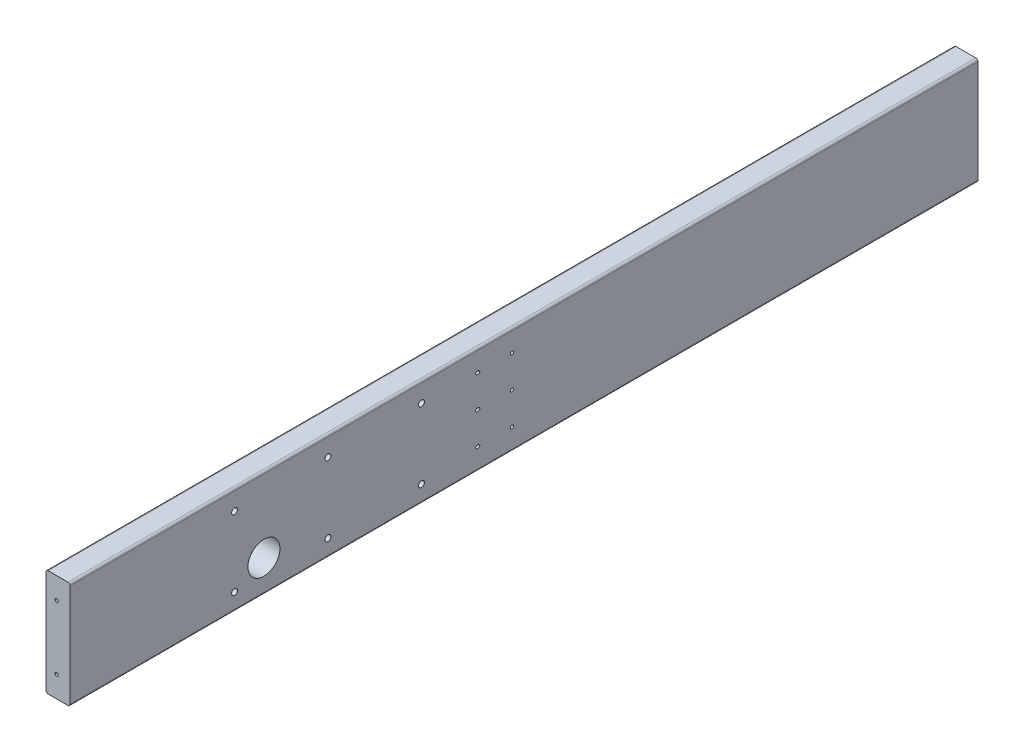
SolidWorks part; units mm, degrees
material "Beech"
ref_plane "Front Plane" through (0, 0, 0) normal (0, 0, 1) x (1, 0, 0)
ref_plane "Top Plane" through (0, 0, 0) normal (0, 1, 0) x (1, 0, 0)
ref_plane "Right Plane" through (0, 0, 0) normal (1, 0, 0) x (0, 0, -1)
sketch "Sketch1" plane through (0, 0, 0) normal (0, 0, 1) x (1, 0, 0)
  line L0 (-31.1883, 134.2727) -> (-31.1883, -65.7273)
  line L1 (-31.1883, -65.7273) -> (13.8117, -65.7273)
  line L2 (-31.1883, 134.2727) -> (13.8117, 134.2727)
  line L3 (13.8117, 134.2727) -> (13.8117, -65.7273)
extrude "Boss-Extrude1" add sketch "Sketch1" along normal blind 1700
fillet "Fillet1" radius 4 4 edges at (-31.1883, -65.7273, 850) (13.8117, -65.7273, 850) (-31.1883, 134.2727, 850) (13.8117, 134.2727, 850)
sketch "Sketch9" plane through (13.8117, 0, 0) normal (1, 0, 0) x (0, 0, -1)
  circle A0 centre (-1337, -5.7273) radius 30
extrude "Cut-Extrude1" cut sketch "Sketch9" against normal blind 50
sketch "Sketch10" plane through (13.8117, 0, 0) normal (1, 0, 0) x (0, 0, -1)
  circle A0 centre (-1392, 97.2727) radius 5.5
extrude "Cut-Extrude2" cut sketch "Sketch10" against normal blind 50
sketch "Sketch11" plane through (13.8117, 0, 0) normal (1, 0, 0) x (0, 0, -1)
  circle A0 centre (-1392, -33.7273) radius 5.5
extrude "Cut-Extrude3" cut sketch "Sketch11" against normal blind 50
sketch "Sketch12" plane through (13.8117, 0, 0) normal (1, 0, 0) x (0, 0, -1)
  circle A0 centre (-1217, 97.2727) radius 5.5
extrude "Cut-Extrude4" cut sketch "Sketch12" against normal blind 50
sketch "Sketch13" plane through (13.8117, 0, 0) normal (1, 0, 0) x (0, 0, -1)
  circle A0 centre (-1217, -33.7273) radius 5.5
extrude "Cut-Extrude5" cut sketch "Sketch13" against normal blind 50
sketch "Sketch14" plane through (13.8117, 0, 0) normal (1, 0, 0) x (0, 0, -1)
  circle A0 centre (-1042, -33.7273) radius 5.5
extrude "Cut-Extrude6" cut sketch "Sketch14" against normal blind 50
sketch "Sketch15" plane through (13.8117, 0, 0) normal (1, 0, 0) x (0, 0, -1)
  circle A0 centre (-1042, 97.2727) radius 5.5
extrude "Cut-Extrude7" cut sketch "Sketch15" against normal blind 50
sketch "Sketch16" plane through (-31.1883, 0, 0) normal (-1, 0, 0) x (0, 0, 1)
  line L0 (0, 130.2727) -> (0, -61.7273) construction
  line L1 (1700, 130.2727) -> (0, 130.2727) construction
  line L2 (1700, -65.7273) -> (0, -65.7273) construction
  circle A0 centre (50, -25.7273) radius 18
  circle A1 centre (50, 34.2727) radius 18
  circle A2 centre (50, 91.2727) radius 18
  dimension "D1" = 36
  dimension "D2" = 36
  dimension "D3" = 36
  dimension "D4" = 50
  dimension "D5" = 50
  dimension "D6" = 50
  dimension "D7" = 39
  dimension "D8" = 40
  dimension "D9" = 100
extrude "Cut-Extrude8" cut sketch "Sketch16" against normal blind 30
hole_wizard "Ø8.0mm Dowel Slot3" positions "Sketch19" profile "Sketch20" size "Ø8.0" standard "ISO"
sketch "Sketch19" plane through (793.8117, -65.7273, 0) normal (0, 0, 1) x (1, 0, 0)
  point P0 (-802.5, 40)
  point P2 (-802.5, 100)
  point P4 (-802.5, 157)
sketch "Sketch20" plane through (-8.6883, -25.7273, 0) normal (1, 0, 0) x (0, -1, 0)
  line L0 (0, 0) -> (0, 140)
  line L1 (0, 140) -> (4, 137.5966)
  line L2 (4, 137.5966) -> (4, 0.025)
  line L3 (4, 0.025) -> (4.025, 0)
  line L4 (4.025, 0) -> (0, 0)
  line L5 (-4, 0.025) -> (-4.025, 0) construction
  line L6 (0, 140) -> (-4, 137.5966) construction
  line L7 (0, -6.35) -> (0, 107.95) construction
  dimension "Hole Dia." = 8
  dimension "Hole Depth" = 140
  dimension "Near C'Sink Dia." = 8.05
  dimension "Near C'Sink Angle" = 90
  dimension "Drill Angle" = 118
hole_wizard "Ø6.0mm Dowel Slot" positions "Sketch21" profile "Sketch22" size "Ø6.0" standard "ISO" slot yes
sketch "Sketch21" plane through (-854.1534, -65.7273, 36.0493) normal (-0.7661, 0, 0.6428) x (0.6428, 0, 0.7661)
  line L1 (1244.85, 160) -> (1250.85, 160) construction
  point P0 (1247.85, 160)
  point P2 (1247.85, 100)
  point P4 (1247.85, 40)
sketch "Sketch22" plane through (-52.0862, 94.2727, 991.9875) normal (0, 1, 0) x (0.6428, 0, 0.7661)
  line L0 (0, 0) -> (0, 130)
  line L1 (0, 130) -> (3, 128.1974)
  line L2 (3, 128.1974) -> (3, 0.025)
  line L3 (3, 0.025) -> (3.025, 0)
  line L4 (3.025, 0) -> (0, 0)
  line L5 (-3, 0.025) -> (-3.025, 0) construction
  line L6 (0, 130) -> (-3, 128.1974) construction
  line L7 (0, -6.35) -> (0, 107.95) construction
  dimension "Hole Dia." = 6
  dimension "Hole Depth" = 130
  dimension "Near C'Sink Dia." = 6.05
  dimension "Near C'Sink Angle" = 90
  dimension "Drill Angle" = 118
hole_wizard "Ø6.0mm Dowel Slot1" positions "Sketch23" profile "Sketch24" size "Ø6.0" standard "ISO" slot yes
sketch "Sketch23" plane through (13.8117, -65.7273, 0) normal (1, 0, 0) x (0, 0, -1)
  point P0 (-872.5, 160)
  point P2 (-872.5, 100)
  point P4 (-872.5, 40)
sketch "Sketch24" plane through (13.8117, 94.2727, 872.5) normal (0, 1, 0) x (0, 0, -1)
  line L0 (0, 0) -> (0, 65)
  line L1 (0, 65) -> (3, 63.1974)
  line L2 (3, 63.1974) -> (3, 0.025)
  line L3 (3, 0.025) -> (3.025, 0)
  line L4 (3.025, 0) -> (0, 0)
  line L5 (-3, 0.025) -> (-3.025, 0) construction
  line L6 (0, 65) -> (-3, 63.1974) construction
  line L7 (0, -6.35) -> (0, 107.95) construction
  dimension "Hole Dia." = 6
  dimension "Hole Depth" = 65
  dimension "Near C'Sink Dia." = 6.05
  dimension "Near C'Sink Angle" = 90
  dimension "Drill Angle" = 118
sketch "Sketch25" plane through (-31.1883, 0, 0) normal (-1, 0, 0) x (0, 0, 1)
  line L0 (1700, 130.2727) -> (1700, -61.7273) construction
  line L1 (0, 134.2727) -> (1700, 134.2727) construction
  line L2 (1700, -65.7273) -> (0, -65.7273) construction
  circle A1 centre (1650, 94.2727) radius 18
  circle A2 centre (1650, -25.7273) radius 18
  dimension "D1" = 36
  dimension "D2" = 36
  dimension "D3" = 50
  dimension "D4" = 50
  dimension "D5" = 40
  dimension "D6" = 40
extrude "Cut-Extrude9" cut sketch "Sketch25" against normal blind 30
hole_wizard "Ø6.0mm Dowel Slot2" positions "Sketch26" profile "Sketch27" size "Ø6.0" standard "ISO" slot yes
sketch "Sketch26" plane through (-811.1883, -65.7273, 1700) normal (0, 0, 1) x (1, 0, 0)
  point P0 (25, 160)
  point P2 (25, 40)
  point P11 (800, 160)
  point P13 (800, 40)
sketch "Sketch27" plane through (-786.1883, 94.2727, 1700) normal (1, 0, 0) x (0, -1, 0)
  line L0 (0, 0) -> (0, 50)
  line L1 (0, 50) -> (3, 48.1974)
  line L2 (3, 48.1974) -> (3, 0.025)
  line L3 (3, 0.025) -> (3.025, 0)
  line L4 (3.025, 0) -> (0, 0)
  line L5 (-3, 0.025) -> (-3.025, 0) construction
  line L6 (0, 50) -> (-3, 48.1974) construction
  line L7 (0, -6.35) -> (0, 107.95) construction
  dimension "Hole Dia." = 6
  dimension "Hole Depth" = 50
  dimension "Near C'Sink Dia." = 6.05
  dimension "Near C'Sink Angle" = 90
  dimension "Drill Angle" = 118
hole_wizard "Ø8.0mm Dowel Slot4" positions "Sketch30" profile "Sketch31" size "Ø8.0" standard "ISO" slot yes
sketch "Sketch30" plane through (-811.1883, -65.7273, -90) normal (0, 0, -1) x (-1, 0, 0)
  point P0 (-802.5, 40)
  point P2 (-802.5, 100)
  point P4 (-802.5, 157)
sketch "Sketch31" plane through (-8.6883, -25.7273, -90) normal (1, 0, 0) x (0, 1, 0)
  line L0 (0, 0) -> (0, 140)
  line L1 (0, 140) -> (4, 137.5966)
  line L2 (4, 137.5966) -> (4, 0.025)
  line L3 (4, 0.025) -> (4.025, 0)
  line L4 (4.025, 0) -> (0, 0)
  line L5 (-4, 0.025) -> (-4.025, 0) construction
  line L6 (0, 140) -> (-4, 137.5966) construction
  line L7 (0, -6.35) -> (0, 107.95) construction
  dimension "Hole Dia." = 8
  dimension "Hole Depth" = 140
  dimension "Near C'Sink Dia." = 8.05
  dimension "Near C'Sink Angle" = 90
  dimension "Drill Angle" = 118
ref_plane "Plane1" through (0, 34.2727, 0) normal (0, 1, 0) x (1, 0, 0)
hole_wizard "Ø6.0mm Dowel Slot4" positions "Sketch34" profile "Sketch35" size "Ø6.0" standard "ISO"
sketch "Sketch34" plane through (-811.1883, 146.2727, 0) normal (0, 1, 0) x (1, 0, 0)
  point P0 (22.5, 1812.5)
  point P3 (22.5, 1777.0533)
  point P7 (802.5, 1812.5)
  point P10 (802.5, 1787.0555)
  point P14 (22.5608, 973.75)
  point P17 (22.5608, 951.25)
  point P20 (802.5608, 973.75)
  point P23 (802.5608, 951.25)
  point P26 (22.5, -1455.8975)
  point P28 (802.5, -1462.0727)
  point P30 (802.5, -861.25)
  point P33 (802.5, -883.75)
  point P36 (22.5, -861.25)
  point P39 (22.5, -883.75)
  point P42 (22.5, 67.5)
  point P46 (22.5, 22.5)
  point P50 (802.5, 67.5)
  point P52 (802.5, 22.5)
sketch "Sketch35" plane through (-788.6883, 146.2727, -1812.5) normal (1, 0, 0) x (0, 0, 1)
  line L0 (0, 0) -> (0, 30)
  line L1 (0, 30) -> (3, 28.1974)
  line L2 (3, 28.1974) -> (3, 0.025)
  line L3 (3, 0.025) -> (3.025, 0)
  line L4 (3.025, 0) -> (0, 0)
  line L5 (-3, 0.025) -> (-3.025, 0) construction
  line L6 (0, 30) -> (-3, 28.1974) construction
  line L7 (0, -6.35) -> (0, 107.95) construction
  dimension "Hole Dia." = 6
  dimension "Hole Depth" = 30
  dimension "Near C'Sink Dia." = 6.05
  dimension "Near C'Sink Angle" = 90
  dimension "Drill Angle" = 118
hole_wizard "Ø6.0mm Dowel Slot6" positions "Sketch38" profile "Sketch39" size "Ø6.0" standard "ISO"
sketch "Sketch38" plane through (-811.1883, 146.2727, 0) normal (0, 1, 0) x (1, 0, 0)
  point P0 (22.5, 1726.5)
  point P4 (22.5, 1640.5)
  point P6 (802.5, 1726.5)
  point P10 (802.5, 1640.5)
  point P12 (22.5, -955.9606)
  point P14 (22.5, -1636.5)
  point P16 (802.5, -1462.5)
  point P18 (802.5, -1636.5)
  point P19 (22.5, -1722.5)
  point P22 (802.5, -1722.5)
  point P25 (22.5, -1550.5)
  point P27 (802.5, -778.9107)
  point P33 (120, -1722.5)
  point P37 (217.5, -1722.5)
  point P39 (315, -1722.5)
  point P41 (412.5, -1722.5)
  point P43 (510, -1722.5)
  point P45 (607.5, -1722.5)
  point P48 (705, -1722.5)
  point P51 (22.5, -861.25)
  point P54 (22.5, -883.75)
  point P57 (-22.4962, -917.6022)
  point P60 (802.5, -861.25)
  point P63 (802.5, -883.75)
  point P66 (847.4962, -917.6022)
  point P69 (802.5, -536.8366)
  point P71 (22.5, -750.2496)
  point P73 (-341.0052, -650.3187)
  point P76 (1166.0052, -650.3187)
  point P79 (2543.5014, 245.8654)
  point P82 (-501.5002, -524.8138)
  point P85 (-310.0849, -433.3306)
  point P88 (-310.0849, -388.3306)
  point P91 (22.5, -388.3306)
  point P95 (22.5, -433.3306)
  point P99 (802.5, -388.3306)
  point P101 (802.5, -433.3306)
  point P103 (1133.73, -388.3306)
  point P106 (1133.73, -433.3306)
  point P109 (2543.5014, -171.034)
  point P112 (1166.0052, 740.3187)
  point P115 (802.5608, 951.25)
  point P118 (802.5608, 951.25)
  point P121 (847.4962, 1007.6022)
  point P124 (-22.4962, 1007.6022)
  point P127 (22.5608, 951.25)
  point P130 (22.5608, 951.25)
  point P133 (-341.0052, 740.3187)
  point P136 (-501.5002, 393.1551)
  point P139 (22.5, 1812.5)
  point P142 (802.5, 1812.5)
  point P148 (22.5, 1552.5)
  point P150 (802.5, 1552.5)
  point P155 (22.5, 83.8102)
  point P157 (802.5, 297.2232)
  point P160 (-102.162, -850.749)
  point P164 (-181.8278, -783.8957)
  point P166 (-261.4937, -717.0425)
  point P168 (927.162, -850.749)
  point P172 (1006.8278, -783.8957)
  point P174 (1086.4937, -717.0425)
  point P176 (1086.4937, 807.0425)
  point P180 (1006.8278, 873.8957)
  point P182 (927.162, 940.749)
  point P184 (-102.162, 940.749)
  point P188 (-181.8278, 873.8957)
  point P190 (-261.4937, 807.0425)
  point P193 (-199.2249, -388.3306)
  point P195 (-88.3649, -388.3306)
  point P197 (-199.2249, -433.3306)
  point P199 (-88.3649, -433.3306)
  point P201 (912.01, -388.3306)
  point P203 (1022.87, -388.3306)
  point P205 (912.01, -433.3306)
  point P207 (1022.87, -433.3306)
  point P209 (-501.5002, -424.1138)
  point P213 (-501.5002, -323.4138)
  point P217 (-501.5002, -222.7138)
  point P219 (-501.5002, -307.2046)
  point P221 (-501.5002, -122.0138)
  point P223 (-501.5002, -21.3138)
  point P225 (-501.5002, 79.3862)
  point P227 (-501.5002, 180.0862)
  point P229 (-501.5002, 280.7862)
  point P231 (-501.5002, 381.4862)
  point P237 (-501.5002, 482.1862)
  point P239 (-501.5002, 582.8862)
  point P241 (-501.5002, 683.5862)
  point P242 (2543.5014, 145.1654)
  point P246 (2543.5014, 44.4654)
  point P248 (2543.5014, -56.2346)
  point P250 (2543.5014, -156.9346)
  point P252 (2543.5014, -257.6346)
  point P254 (2543.5014, -358.3346)
  point P256 (2543.5014, -459.0346)
  point P258 (2543.5014, -559.7346)
  point P260 (2543.5014, -660.4346)
  point P262 (2543.5014, -761.1346)
  point P264 (2543.5014, -861.8346)
  point P266 (2543.5014, -962.5346)
  point P268 (120, -388.3306)
  point P270 (217.5, -388.3306)
  point P272 (315, -388.3306)
  point P274 (592.3435, -336.1213)
  point P276 (607.5, -388.3306)
  point P278 (705, -388.3306)
  point P283 (510, -388.3306)
  point P292 (120, -433.3306)
  point P294 (217.5, -433.3306)
  point P296 (315, -433.3306)
  point P300 (510, -433.3306)
  point P302 (607.5, -433.3306)
  point P304 (705, -433.3306)
  point P307 (412.5, -433.3306)
  point P309 (22.5, -750.78)
  point P311 (22.5, -640.31)
  point P313 (22.5, -529.84)
  point P315 (22.5, -419.37)
  point P317 (22.5, -308.9)
  point P319 (22.5, -198.43)
  point P321 (22.5, -87.96)
  point P324 (802.5, -750.78)
  point P326 (802.5, -402.8046)
  point P328 (802.5, -357.1566)
  point P330 (802.5, -311.5085)
  point P332 (802.5, -265.8604)
  point P334 (802.5, -220.2123)
  point P336 (802.5, -174.5642)
  point P337 (22.5, -277.8606)
  point P339 (22.5, -167.3906)
  point P341 (22.5, -56.9206)
  point P343 (22.5, 53.5494)
  point P345 (22.5, 164.0194)
  point P347 (22.5, 274.4894)
  point P349 (22.5, 384.9594)
  point P352 (802.5, -64.6773)
  point P354 (802.5, -19.0293)
  point P356 (802.5, 72.2669)
  point P358 (802.5, 26.2178)
  point P360 (802.5, 117.915)
  point P362 (802.5, 228.385)
  point P364 (802.5, 209.2112)
  point P365 (1224.4002, 2039.7886)
  point P369 (1161.3433, 1965.4241)
  point P373 (1089.7554, 1899.2318)
  point P375 (1008.8996, 1844.747)
  point P377 (920.7821, 1803.0151)
  point P379 (823.4819, 1796.7769)
  point P381 (755.0534, 1727.3233)
  point P386 (120.0608, 951.25)
  point P390 (217.5608, 951.25)
  point P392 (315.0608, 951.25)
  point P397 (412.5608, 951.25)
  point P399 (510.0608, 951.25)
  point P401 (607.5608, 951.25)
  point P404 (705.0608, 951.25)
  point P406 (656.3108, 951.25)
  point P410 (558.8108, 951.25)
  point P412 (461.3108, 951.25)
  point P414 (363.8108, 951.25)
  point P421 (266.3108, 951.25)
  point P423 (168.8108, 951.25)
  point P426 (120, -861.25)
  point P430 (217.5, -861.25)
  point P432 (315, -861.25)
  point P434 (412.5, -861.25)
  point P436 (510, -861.25)
  point P438 (607.5, -861.25)
  point P440 (705, -861.25)
  point P446 (656.25, -883.75)
  point P450 (558.75, -883.75)
  point P452 (461.25, -883.75)
  point P454 (168.75, -883.75)
  point P456 (266.25, -883.75)
  point P458 (363.75, -883.75)
sketch "Sketch39" plane through (-788.6883, 146.2727, -1726.5) normal (1, 0, 0) x (0, 0, 1)
  line L0 (0, 0) -> (0, 30)
  line L1 (0, 30) -> (3, 28.1974)
  line L2 (3, 28.1974) -> (3, 0.025)
  line L3 (3, 0.025) -> (3.025, 0)
  line L4 (3.025, 0) -> (0, 0)
  line L5 (-3, 0.025) -> (-3.025, 0) construction
  line L6 (0, 30) -> (-3, 28.1974) construction
  line L7 (0, -6.35) -> (0, 107.95) construction
  dimension "Hole Dia." = 6
  dimension "Hole Depth" = 30
  dimension "Near C'Sink Dia." = 6.05
  dimension "Near C'Sink Angle" = 90
  dimension "Drill Angle" = 118
